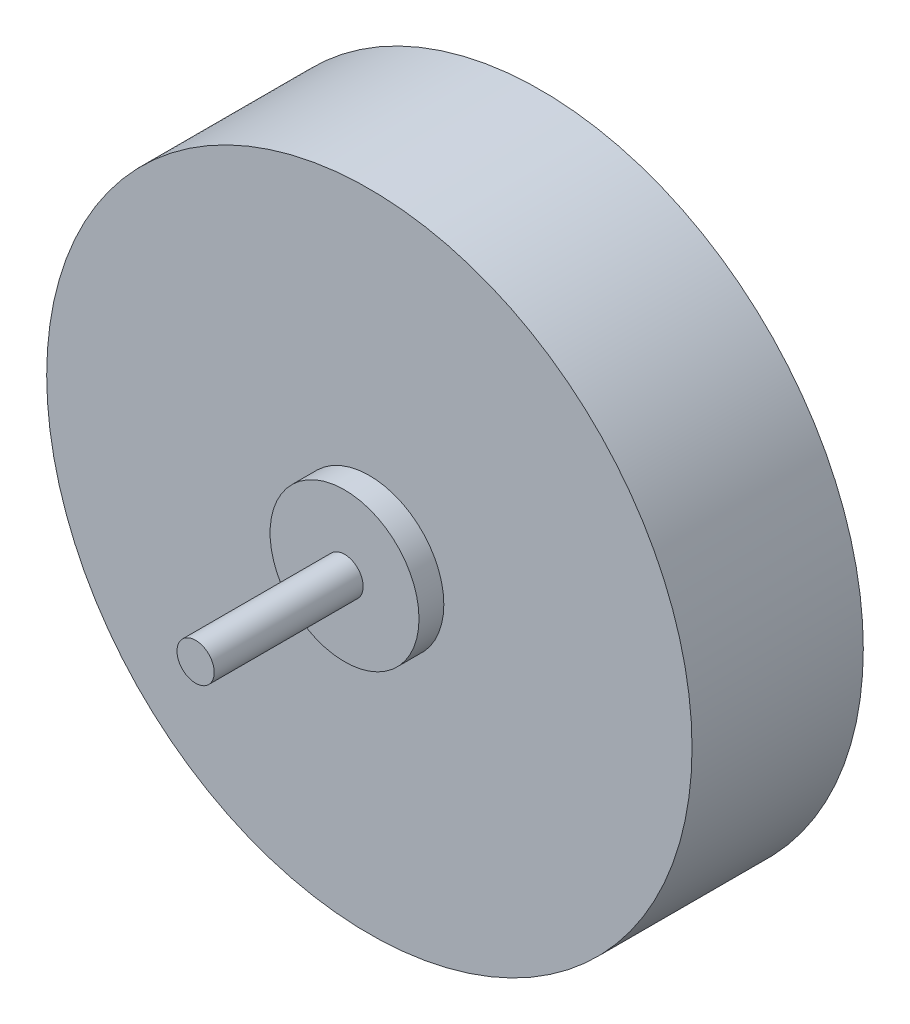
SolidWorks part; units mm, degrees
ref_plane "Plan de face" through (0, 0, 0) normal (0, 0, 1) x (1, 0, 0)
ref_plane "Plan de dessus" through (0, 0, 0) normal (0, 1, 0) x (1, 0, 0)
ref_plane "Plan de droite" through (0, 0, 0) normal (1, 0, 0) x (0, 0, -1)
sketch "Esquisse1" plane through (0, 0, 0) normal (0, 0, 1) x (1, 0, 0)
  circle A0 centre (0, 0) radius 13
  dimension "D1" = 26
extrude "Boss.-Extru.1" add sketch "Esquisse1" along normal blind 6.9
sketch "Esquisse2" plane through (0, 0, 6.9) normal (0, 0, 1) x (1, 0, 0)
  circle A0 centre (0, 0) radius 3
  circle A1 centre (0, 0) radius 13 construction
  dimension "D1" = 6
extrude "Boss.-Extru.2" add sketch "Esquisse2" along normal blind 1
sketch "Esquisse3" plane through (0, 0, 7.9) normal (0, 0, 1) x (1, 0, 0)
  circle A0 centre (0, 0) radius 0.75
  dimension "D1" = 1.5
extrude "Boss.-Extru.3" add sketch "Esquisse3" along normal blind 6
sketch "Esquisse4" plane through (0, 0, 0) normal (0, 0, -1) x (-1, 0, 0)
  circle A0 centre (0, 0) radius 3
  dimension "D1" = 6
extrude "Boss.-Extru.4" add sketch "Esquisse4" along normal blind 2.3
sketch "Esquisse5" plane through (0, 0, 0) normal (0, 0, -1) x (-1, 0, 0)
  circle A0 centre (0, 0) radius 0.75
  dimension "D1" = 1.5
